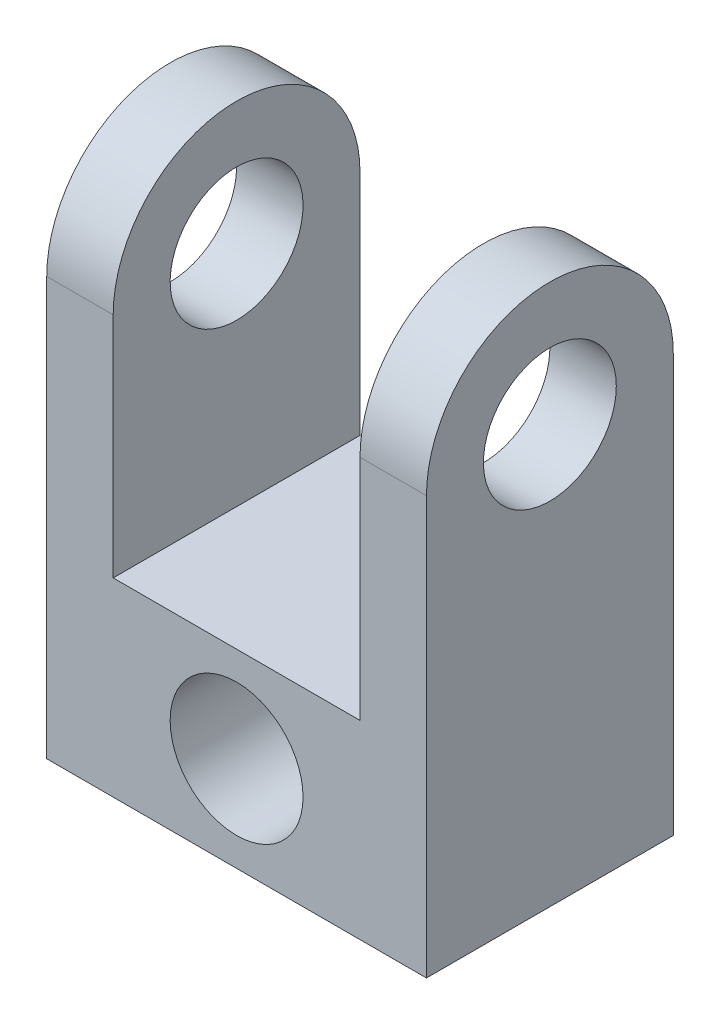
SolidWorks part; units mm, degrees
ref_plane "Plano frontal" through (0, 0, 0) normal (0, 0, 1) x (1, 0, 0)
ref_plane "Plano superior" through (0, 0, 0) normal (0, 1, 0) x (1, 0, 0)
ref_plane "Plano direito" through (0, 0, 0) normal (1, 0, 0) x (0, 0, -1)
sketch "Esboço1" plane through (0, 0, 0) normal (1, 0, 0) x (0, 0, -1)
  line L1 (-6.5, 0) -> (-6.5, -22)
  line L2 (6.5, 0) -> (6.5, -22)
  line L3 (-6.5, -22) -> (6.5, -22)
  arc A0 (6.5, 0) -> (-6.5, 0) centre (0, 0) ccw
  circle A1 centre (0, 0) radius 3.5
  dimension "D1" = 13
  dimension "D3" = 7
  dimension "D2" = 22
extrude "Ressalto-extrusão1" add sketch "Esboço1" along normal mid plane 20
sketch "Esboço2" plane through (0, 0, 0) normal (0, 0, 1) x (1, 0, 0)
  line L0 (0, 0) -> (0, -22) construction
  line L1 (10, -22) -> (-10, -22) construction
  line L2 (10, 0) -> (-10, 0) construction
  circle A0 centre (0, -17) radius 3.5
  dimension "D1" = 7
  dimension "D2" = 17
extrude "Corte-extrusão1" cut sketch "Esboço2" against normal mid plane 20
sketch "Esboço3" plane through (0, 0, 0) normal (0, 0, 1) x (1, 0, 0)
  line L0 (0, 6.5) -> (0, 0) construction
  line L1 (10, 6.5) -> (-10, 6.5) construction
  line L2 (0, 0) -> (0, -22) construction
  line L3 (10, -22) -> (-10, -22) construction
  line L6 (-6.5, 6.5) -> (6.5, 6.5)
  line L7 (-6.5, 6.5) -> (-6.5, -12)
  line L8 (6.5, 6.5) -> (6.5, -12)
  line L9 (-6.5, -12) -> (6.5, -12)
  dimension "D1" = 6.5
  dimension "D2" = 12
extrude "Corte-extrusão2" cut sketch "Esboço3" against normal mid plane 20
